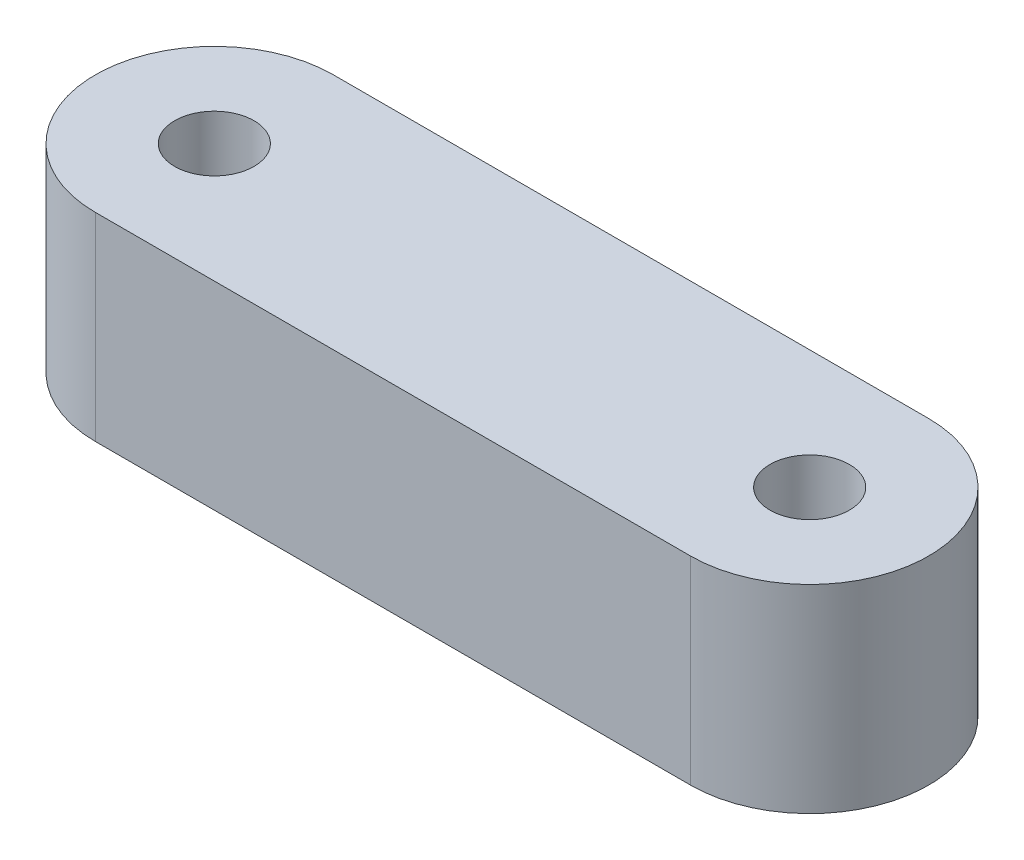
SolidWorks part; units mm, degrees
ref_plane "Front Plane" through (0, 0, 0) normal (0, 0, 1) x (1, 0, 0)
ref_plane "Top Plane" through (0, 0, 0) normal (0, 1, 0) x (1, 0, 0)
ref_plane "Right Plane" through (0, 0, 0) normal (1, 0, 0) x (0, 0, -1)
sketch "Sketch3" plane through (0, 0, 0) normal (0, 1, 0) x (1, 0, 0)
  line L0 (-63.5, 0) -> (-25.4, 0) construction
  line L1 (-6.985, 0) -> (6.985, 0) construction
  line L2 (-63.5, 7.62) -> (-25.4, 7.62)
  line L3 (-63.5, -7.62) -> (-25.4, -7.62)
  arc A0 (-63.5, 7.62) -> (-63.5, -7.62) centre (-63.5, 0) ccw
  arc A1 (-25.4, -7.62) -> (-25.4, 7.62) centre (-25.4, 0) ccw
  point P5 (-44.45, 0)
  dimension "D2" = 7.62
  dimension "D1" = 38.1
  dimension "D3" = 63.5
extrude "Boss-Extrude1" add sketch "Sketch3" along normal blind 12.7
sketch "Sketch4" plane through (0, 12.7, 0) normal (0, 1, 0) x (1, 0, 0)
  circle A0 centre (-63.5, 0) radius 2.54
  circle A1 centre (-25.4, 0) radius 2.54
  dimension "D1" = 5.08
extrude "Cut-Extrude3" cut sketch "Sketch4" against normal through all
equation "\"TibiaLength\"= 5in"
equation "\"TibiaRadius\"= 0.3in"
equation "\"TibiaDistFromCentre\"= \"TibiaLength\" / 2"
equation "\"TibiaThickness\"= 0.5in"
equation "\"HoleRadius\"= 0.2in"
equation "\"D1@Sketch3\"= \"TibiaLength\" * 0.3"
equation "\"D2@Sketch3\"= \"TibiaRadius\""
equation "\"D3@Sketch3\"= \"TibiaDistFromCentre\""
equation "\"D1@Boss-Extrude1\"= \"TibiaThickness\""
equation "\"D1@Sketch4\"= \"HoleRadius\""
